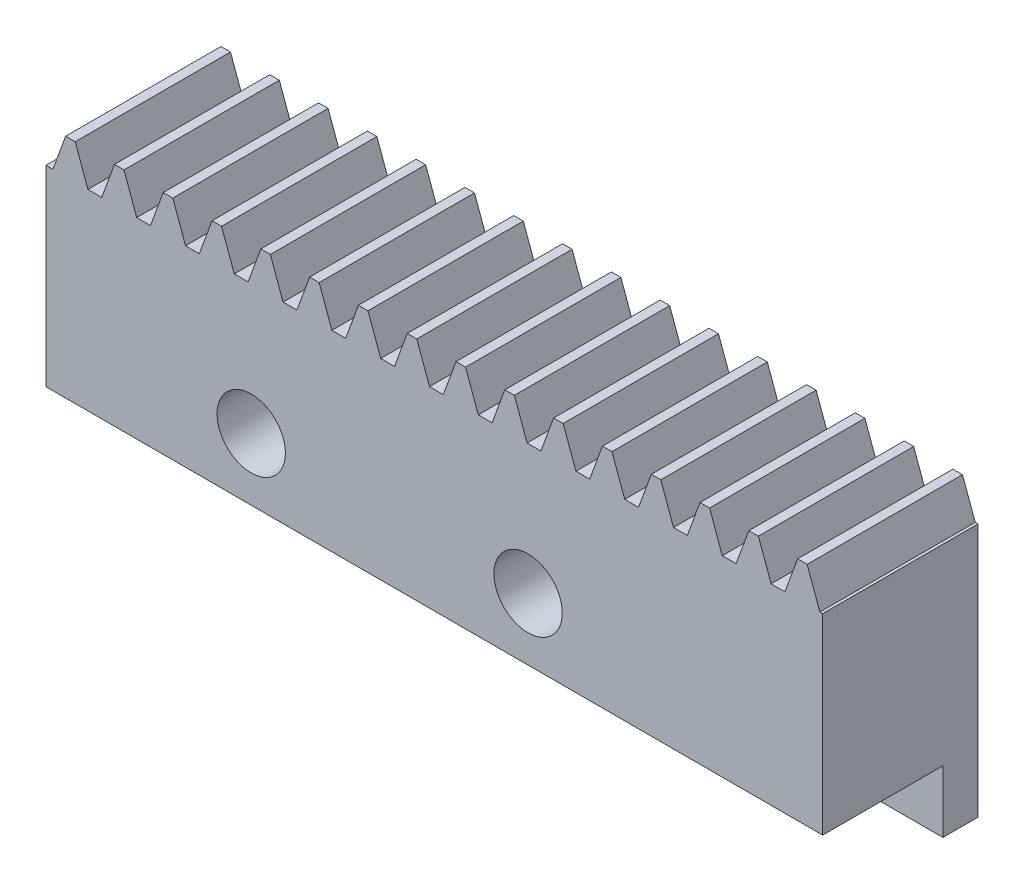
SolidWorks part; units mm, degrees
extrude "Blank" add sketch "BlankSke" against normal blind 4
sketch "BlankSke" plane through (0, 0, 0) normal (0, 0, 1) x (1, 0, 0)
  line L1 (0, 0) -> (25, 0)
  line L2 (0, 0) -> (0, 7.3)
  line L3 (0, 7.3) -> (25, 7.3)
  line L4 (25, 0) -> (25, 7.3)
  dimension "Length" = 25
  dimension "Blank_height" = 7.3
ref_plane "Plane1" through (0, 0, 0) normal (0, 0, 1) x (1, 0, 0)
ref_plane "Plane2" through (0, 0, 0) normal (0, 1, 0) x (1, 0, 0)
ref_plane "Plane3" through (0, 0, 0) normal (1, 0, 0) x (0, 0, -1)
sketch "HoldingSke" plane through (0, 0, 0) normal (0, 1, 0) x (1, 0, 0)
  line L0 (0, 0) -> (0.2783, 1.9805)
  line L1 (-15, 0) -> (100, 0) construction
  line L2 (0, 0) -> (-2.1039, 2.3779)
  line L3 (0, 0) -> (-11.863, 4.5341)
  line L4 (0, 0) -> (8.2587, 2.5249)
  line L5 (0, 0) -> (-23.7986, -8.8762)
  line L6 (0, 0) -> (-10.5278, -7.1032)
  line L9 (-71.009, 38.7566) -> (-47.5167, 47.3071)
  line L10 (-76.2, 2.8779) -> (-69.4, 2.8779)
  line L11 (0, 0) -> (-4, 0)
  line L12 (-76.2, 101.6) -> (-76.181, 101.6)
  line L13 (24.9733, 27.94) -> (52.9518, 28.4284)
  line L14 (24.9733, 27.94) -> (24.9743, 27.94)
  line L15 (24.9733, 27.94) -> (100.4006, 29.5858)
  circle A0 centre (0, 0) radius 19.05
  circle A1 centre (0, 0) radius 3.4
  circle A2 centre (0, 0) radius 12.7
  dimension "MPH" = 6.8
  dimension "Diameter" = 38.1
  dimension "Num_teeth" = 17
  dimension "Pitch" = 2
  dimension "Show_teeth" = 998
  dimension "Thickness" = 12.7
  dimension "Ap" = 20
  dimension "Pitch_height" = 6.8
  dimension "Width" = 4
  dimension "Backlash" = 0.019
  dimension "Addendum_fac" = 1
  dimension "Dedendum_fac" = 1.25
  dimension "Clearance_fac" = 0.25
  dimension "Dedendum_add" = 0.001
  dimension "Length" = 25
  dimension "Module" = 0.5
sketch "TooCutSkeIll" plane through (0, 0, 0) normal (0, 0, 1) x (1, 0, 0)
  line L0 (-0.6269, 7.2868) -> (-0.2524, 6.2579)
  line L1 (-0.134, 6.175) -> (0.134, 6.175)
  line L2 (0.2524, 6.2579) -> (0.6269, 7.2868)
  line L3 (25, 7.3) -> (0, 7.3) construction
  line L4 (0, 0) -> (0, 64.897) construction
  line L5 (-13.208, 6.8) -> (12.954, 6.8) construction
  line L6 (0, 0) -> (25, 0) construction
  line L7 (0.4497, 6.8) -> (0.4497, 48.7463) construction
  line L8 (-0.4497, 6.8) -> (-0.4497, 48.7463) construction
  line L9 (0.6457, 7.3) -> (0.6457, 7.3254)
  line L10 (-0.6457, 7.3) -> (-0.6457, 7.3254)
  line L11 (-0.6457, 7.3254) -> (0.6457, 7.3254)
  arc A0 (0.134, 6.175) -> (0.2524, 6.2579) centre (0.134, 6.301) ccw
  arc A1 (-0.2524, 6.2579) -> (-0.134, 6.175) centre (-0.134, 6.301) ccw
  arc A2 (0.6457, 7.3) -> (0.6269, 7.2868) centre (0.6457, 7.28) ccw
  arc A3 (-0.6269, 7.2868) -> (-0.6457, 7.3) centre (-0.6457, 7.28) ccw
  dimension "Pitch_height" = 6.8
  dimension "Addendum_plus" = 0.5254
  dimension "Pressure_angle" = 20
  dimension "Gap_width" = 0.8994
  dimension "Dedendum" = 0.625
extrude "ToothCutIll" [suppressed] cut sketch "TooCutSkeIll" against normal through all
sketch "TooCutSkeSim" plane through (0, 0, 0) normal (0, 0, 1) x (1, 0, 0)
  line L0 (0.2222, 6.175) -> (-0.2222, 6.175)
  line L1 (0.6409, 7.3254) -> (0.2222, 6.175)
  line L2 (0, 17.4625) -> (0, 53.467) construction
  line L3 (0.6409, 7.3254) -> (-0.6409, 7.3254)
  line L6 (-0.6409, 7.3254) -> (-0.2222, 6.175)
  line L9 (-0.4497, 6.8) -> (0.4497, 6.8) construction
  line L10 (0, 0) -> (25, 0) construction
  line L11 (0.4497, 6.8) -> (0.4497, 53.467) construction
  line L12 (-0.4497, 6.8) -> (-0.4497, 53.467) construction
  dimension "Pitch_height" = 6.8
  dimension "Addendum_plus" = 0.5254
  dimension "Pressure_angle" = 20
  dimension "Gap_width" = 0.8994
  dimension "Dedendum" = 0.625
extrude "ToothCutSim" cut sketch "TooCutSkeSim" against normal through all
pattern_linear "TeethCuts" count 17 spacing 1.5708 along (1, 0, 0) of "ToothCutIll", "ToothCutSim"
sketch "Sketch4" plane through (0, 0, 0) normal (0, -1, 0) x (1, 0, 0)
  line L0 (0, -50) -> (0, 50) construction
  line L1 (0, -4) -> (25, -4)
  line L2 (0, -4) -> (0, -2.87)
  line L3 (0, -2.87) -> (25, -2.87)
  line L4 (25, -4) -> (25, -2.87)
  line L5 (0, -4) -> (25, -4) construction
  line L6 (25, -4) -> (25, 0) construction
  dimension "D1" = 1.13
extrude "Boss-Extrude1" add sketch "Sketch4" along normal blind 2
sketch "Sketch7" plane through (0, 0, 0) normal (0, 0, 1) x (1, 0, 0)
  line L68 (25, 6.175) -> (24.9105, 6.175)
  line L69 (24.9105, 6.175) -> (24.5011, 7.3)
  line L70 (24.5011, 7.3) -> (24.1936, 7.3)
  line L71 (24.1936, 7.3) -> (23.7842, 6.175)
  line L72 (23.7842, 6.175) -> (23.3397, 6.175)
  line L73 (23.3397, 6.175) -> (22.9303, 7.3)
  line L74 (22.9303, 7.3) -> (22.6228, 7.3)
  line L75 (22.6228, 7.3) -> (22.2134, 6.175)
  line L76 (22.2134, 6.175) -> (21.7689, 6.175)
  line L77 (21.7689, 6.175) -> (21.3595, 7.3)
  line L78 (21.3595, 7.3) -> (21.052, 7.3)
  line L79 (21.052, 7.3) -> (20.6426, 6.175)
  line L80 (20.6426, 6.175) -> (20.1981, 6.175)
  line L81 (20.1981, 6.175) -> (19.7887, 7.3)
  line L82 (19.7887, 7.3) -> (19.4812, 7.3)
  line L83 (19.4812, 7.3) -> (19.0718, 6.175)
  line L84 (19.0718, 6.175) -> (18.6273, 6.175)
  line L85 (18.6273, 6.175) -> (18.2179, 7.3)
  line L86 (18.2179, 7.3) -> (17.9104, 7.3)
  line L87 (17.9104, 7.3) -> (17.501, 6.175)
  line L88 (17.501, 6.175) -> (17.0565, 6.175)
  line L89 (17.0565, 6.175) -> (16.6471, 7.3)
  line L90 (16.6471, 7.3) -> (16.3396, 7.3)
  line L91 (16.3396, 7.3) -> (15.9302, 6.175)
  line L92 (15.9302, 6.175) -> (15.4857, 6.175)
  line L93 (15.4857, 6.175) -> (15.0763, 7.3)
  line L94 (15.0763, 7.3) -> (14.7689, 7.3)
  line L95 (14.7689, 7.3) -> (14.3594, 6.175)
  line L96 (14.3594, 6.175) -> (13.9149, 6.175)
  line L97 (13.9149, 6.175) -> (13.5055, 7.3)
  line L98 (13.5055, 7.3) -> (13.1981, 7.3)
  line L99 (13.1981, 7.3) -> (12.7886, 6.175)
  line L100 (12.7886, 6.175) -> (12.3442, 6.175)
  line L101 (12.3442, 6.175) -> (11.9347, 7.3)
  line L102 (11.9347, 7.3) -> (11.6273, 7.3)
  line L103 (11.6273, 7.3) -> (11.2178, 6.175)
  line L104 (11.2178, 6.175) -> (10.7734, 6.175)
  line L105 (10.7734, 6.175) -> (10.3639, 7.3)
  line L106 (10.3639, 7.3) -> (10.0565, 7.3)
  line L107 (10.0565, 7.3) -> (9.647, 6.175)
  line L108 (9.647, 6.175) -> (9.2026, 6.175)
  line L109 (9.2026, 6.175) -> (8.7931, 7.3)
  line L110 (8.7931, 7.3) -> (8.4857, 7.3)
  line L111 (8.4857, 7.3) -> (8.0762, 6.175)
  line L112 (8.0762, 6.175) -> (7.6318, 6.175)
  line L113 (7.6318, 6.175) -> (7.2223, 7.3)
  line L114 (7.2223, 7.3) -> (6.9149, 7.3)
  line L115 (6.9149, 7.3) -> (6.5054, 6.175)
  line L116 (6.5054, 6.175) -> (6.061, 6.175)
  line L117 (6.061, 6.175) -> (5.6515, 7.3)
  line L118 (5.6515, 7.3) -> (5.3441, 7.3)
  line L119 (5.3441, 7.3) -> (4.9346, 6.175)
  line L120 (4.9346, 6.175) -> (4.4902, 6.175)
  line L121 (4.4902, 6.175) -> (4.0807, 7.3)
  line L122 (4.0807, 7.3) -> (3.7733, 7.3)
  line L123 (3.7733, 7.3) -> (3.3638, 6.175)
  line L124 (3.3638, 6.175) -> (2.9194, 6.175)
  line L125 (2.9194, 6.175) -> (2.5099, 7.3)
  line L126 (2.5099, 7.3) -> (2.2025, 7.3)
  line L127 (2.2025, 7.3) -> (1.793, 6.175)
  line L128 (1.793, 6.175) -> (1.3486, 6.175)
  line L129 (1.3486, 6.175) -> (0.9391, 7.3)
  line L130 (0.9391, 7.3) -> (0.6317, 7.3)
  line L131 (0.6317, 7.3) -> (0.2222, 6.175)
  line L132 (0.2222, 6.175) -> (0, 6.175)
  line L133 (0, 6.175) -> (0, 0)
  line L134 (0, 0) -> (25, 0)
  line L135 (25, 0) -> (25, 6.175)
  line L136 (25, 6.175) -> (24.9105, 6.175)
  line L137 (24.9105, 6.175) -> (24.5011, 7.3)
  line L138 (24.5011, 7.3) -> (24.1936, 7.3)
  line L139 (24.1936, 7.3) -> (23.7842, 6.175)
  line L140 (23.7842, 6.175) -> (23.3397, 6.175)
  line L141 (23.3397, 6.175) -> (22.9303, 7.3)
  line L142 (22.9303, 7.3) -> (22.6228, 7.3)
  line L143 (22.6228, 7.3) -> (22.2134, 6.175)
  line L144 (22.2134, 6.175) -> (21.7689, 6.175)
  line L145 (21.7689, 6.175) -> (21.3595, 7.3)
  line L146 (21.3595, 7.3) -> (21.052, 7.3)
  line L147 (21.052, 7.3) -> (20.6426, 6.175)
  line L148 (20.6426, 6.175) -> (20.1981, 6.175)
  line L149 (20.1981, 6.175) -> (19.7887, 7.3)
  line L150 (19.7887, 7.3) -> (19.4812, 7.3)
  line L151 (19.4812, 7.3) -> (19.0718, 6.175)
  line L152 (19.0718, 6.175) -> (18.6273, 6.175)
  line L153 (18.6273, 6.175) -> (18.2179, 7.3)
  line L154 (18.2179, 7.3) -> (17.9104, 7.3)
  line L155 (17.9104, 7.3) -> (17.501, 6.175)
  line L156 (17.501, 6.175) -> (17.0565, 6.175)
  line L157 (17.0565, 6.175) -> (16.6471, 7.3)
  line L158 (16.6471, 7.3) -> (16.3396, 7.3)
  line L159 (16.3396, 7.3) -> (15.9302, 6.175)
  line L160 (15.9302, 6.175) -> (15.4857, 6.175)
  line L161 (15.4857, 6.175) -> (15.0763, 7.3)
  line L162 (15.0763, 7.3) -> (14.7689, 7.3)
  line L163 (14.7689, 7.3) -> (14.3594, 6.175)
  line L164 (14.3594, 6.175) -> (13.9149, 6.175)
  line L165 (13.9149, 6.175) -> (13.5055, 7.3)
  line L166 (13.5055, 7.3) -> (13.1981, 7.3)
  line L167 (13.1981, 7.3) -> (12.7886, 6.175)
  line L168 (12.7886, 6.175) -> (12.3442, 6.175)
  line L169 (12.3442, 6.175) -> (11.9347, 7.3)
  line L170 (11.9347, 7.3) -> (11.6273, 7.3)
  line L171 (11.6273, 7.3) -> (11.2178, 6.175)
  line L172 (11.2178, 6.175) -> (10.7734, 6.175)
  line L173 (10.7734, 6.175) -> (10.3639, 7.3)
  line L174 (10.3639, 7.3) -> (10.0565, 7.3)
  line L175 (10.0565, 7.3) -> (9.647, 6.175)
  line L176 (9.647, 6.175) -> (9.2026, 6.175)
  line L177 (9.2026, 6.175) -> (8.7931, 7.3)
  line L178 (8.7931, 7.3) -> (8.4857, 7.3)
  line L179 (8.4857, 7.3) -> (8.0762, 6.175)
  line L180 (8.0762, 6.175) -> (7.6318, 6.175)
  line L181 (7.6318, 6.175) -> (7.2223, 7.3)
  line L182 (7.2223, 7.3) -> (6.9149, 7.3)
  line L183 (6.9149, 7.3) -> (6.5054, 6.175)
  line L184 (6.5054, 6.175) -> (6.061, 6.175)
  line L185 (6.061, 6.175) -> (5.6515, 7.3)
  line L186 (5.6515, 7.3) -> (5.3441, 7.3)
  line L187 (5.3441, 7.3) -> (4.9346, 6.175)
  line L188 (4.9346, 6.175) -> (4.4902, 6.175)
  line L189 (4.4902, 6.175) -> (4.0807, 7.3)
  line L190 (4.0807, 7.3) -> (3.7733, 7.3)
  line L191 (3.7733, 7.3) -> (3.3638, 6.175)
  line L192 (3.3638, 6.175) -> (2.9194, 6.175)
  line L193 (2.9194, 6.175) -> (2.5099, 7.3)
  line L194 (2.5099, 7.3) -> (2.2025, 7.3)
  line L195 (2.2025, 7.3) -> (1.793, 6.175)
  line L196 (1.793, 6.175) -> (1.3486, 6.175)
  line L197 (1.3486, 6.175) -> (0.9391, 7.3)
  line L198 (0.9391, 7.3) -> (0.6317, 7.3)
  line L199 (0.6317, 7.3) -> (0.2222, 6.175)
  line L200 (0.2222, 6.175) -> (0, 6.175)
  line L201 (0, 6.175) -> (0, 0)
  line L202 (0, 0) -> (25, 0)
  line L203 (25, 0) -> (25, 6.175)
  dimension "D1" = 0
extrude "Boss-Extrude2" add sketch "Sketch7" along normal blind 1
sketch "Sketch8" plane through (0, 0, 1) normal (0, 0, 1) x (1, 0, 0)
  line L0 (6.6057, 2) -> (3.6057, 2) construction
  line L1 (3.6057, 2) -> (18.1057, 2) construction
  line L2 (18.1057, 2) -> (15.5175, 2) construction
  line L3 (15.5175, 2) -> (14.4175, 2) construction
  line L4 (6.6057, 2) -> (3.6057, 2)
  line L5 (3.6057, 2) -> (18.1057, 2)
  line L6 (18.1057, 2) -> (15.5175, 2)
  line L7 (15.5175, 2) -> (14.4175, 2)
  circle A1 centre (15.5175, 2) radius 1.1
  circle A2 centre (15.5175, 2) radius 1.1
  circle A3 centre (15.5175, 2) radius 2.0275
  circle A4 centre (15.5175, 2) radius 2.0275
  circle A5 centre (6.6057, 2) radius 1.1
  circle A6 centre (6.6057, 2) radius 1.1
  dimension "D1" = 0
  dimension "D2" = 0
  dimension "D3" = 0
sketch "Sketch9" plane through (0, 0, 0) normal (0, 0, 1) x (1, 0, 0)
  line L4 (4, 2) -> (1, 2)
  line L5 (1, 2) -> (15.5, 2)
  line L6 (15.5, 2) -> (12.9118, 2)
  line L7 (12.9118, 2) -> (11.8118, 2)
  circle A2 centre (12.9118, 2) radius 1.1
  circle A4 centre (12.9118, 2) radius 2.0275
  circle A6 centre (4, 2) radius 1.1
extrude "Cut-Extrude1" cut sketch "Sketch8" against normal blind 10 contours L5 A2 | L5 A2 | L4 A6 L5 | L5 A6 L4
ref_plane "Plane4" through (0, 0, -4) normal (0, 0, -1) x (-1, 0, 0)
sketch "Sketch10" plane through (0, 0, -4) normal (0, 0, -1) x (-1, 0, 0)
  circle A0 centre (-6.6057, 2) radius 2
extrude "Cut-Extrude3" cut sketch "Sketch10" against normal blind 1
equation "' \"Module@HoldingSke\" = 6.35"
equation "' \"Num_teeth@HoldingSke\" = 12"
equation "' \"Ap@HoldingSke\" =  20"
equation "' \"Ap@HoldingSke\" = 20"
equation "' \"Width@HoldingSke\" = 0.25 * 25.4"
equation "' \"Show_teeth@HoldingSke\" = 500"
equation "' \"Backlash@HoldingSke\" = 0.009 * 25.4"
equation "' \"Addendum_fac@HoldingSke\" = 1.0"
equation "' \"Dedendum_fac@HoldingSke\" = 1.25"
equation "' \"Dedendum_add@HoldingSke\" = 0.00005 * 25.4"
equation "' \"Clearance_fac@HoldingSke\" = 0.25"
equation "' \"Pitch_height@HoldingSke\" = 1 * 25.4"
equation "' \"Length@HoldingSke\" = 4.71 * 25.4"
equation "\"Pitch@HoldingSke\" = 1 / \"Module@HoldingSke\""
equation "\"MPH@HoldingSke\" = \"Dedendum_fac@HoldingSke\" / \"Pitch@HoldingSke\" + 2 * \"Dedendum_add@HoldingSke\" + 0.002 * 25.4"
equation "\"MPH@HoldingSke\" = ((sgn( \"MPH@HoldingSke\" - \"Pitch_height@HoldingSke\")+1)*( \"MPH@HoldingSke\" - \"Pitch_height@HoldingSke\"))/2 + \"Pitch_height@HoldingSke\""
equation "\"Blank_height@BlankSke\" = \"Pitch_height@HoldingSke\" + \"Addendum_fac@HoldingSke\"  / \"Pitch@HoldingSke\" "
equation "\"Length@BlankSke\" =  \"Length@HoldingSke\""
equation "\"Face_width@Blank\" = \"Width@HoldingSke\""
equation "\"Pressure_angle@TooCutSkeIll\" = \"Ap@HoldingSke\""
equation "\"Addendum_plus@TooCutSkeIll\" =  \"Addendum_fac@HoldingSke\"  / \"Pitch@HoldingSke\" + 0.001 *25.4"
equation "\"Dedendum@TooCutSkeIll\" = \"Dedendum_fac@HoldingSke\"  / \"Pitch@HoldingSke\""
equation "\"Pitch_height@TooCutSkeIll\" =  \"MPH@HoldingSke\""
equation "\"Gap_width@TooCutSkeIll\" = 3.14159265 / 2 / \"Pitch@HoldingSke\" + 6 * \"Backlash@HoldingSke\""
equation "\"Pressure_angle@TooCutSkeSim\" = \"Ap@HoldingSke\""
equation "\"Addendum_plus@TooCutSkeSim\" =  \"Addendum_fac@HoldingSke\"  / \"Pitch@HoldingSke\" + 0.001 * 25.4"
equation "\"Dedendum@TooCutSkeSim\" = \"Dedendum_fac@HoldingSke\"  / \"Pitch@HoldingSke\""
equation "\"Pitch_height@TooCutSkeSim\" =  \"MPH@HoldingSke\""
equation "\"Gap_width@TooCutSkeSim\" = 3.14159265 / 2 / \"Pitch@HoldingSke\" + 6 * \"Backlash@HoldingSke\""
equation "\"Root_fillet@TooCutSkeIll\" = \"Clearance_fac@HoldingSke\" / \"Pitch@HoldingSke\" + \"Dedendum_add@HoldingSke\""
equation "\"Break_rad@TooCutSkeIll\" = 0.02 / \"Pitch@HoldingSke\" * 2"
equation "\"Linear_pitch@TeethCuts\" = 3.14159265 / \"Pitch@HoldingSke\""
equation "\"Num_teeth@HoldingSke\" = int( ( \"Length@HoldingSke\" + 0 ) / (3.14159265 / \"Pitch@HoldingSke\")) + 0.9999  + 1"
equation " \"Num_teeth@TeethCuts\" = int( \"Show_teeth@HoldingSke\" ) + 1"
equation " \"Num_teeth@TeethCuts\" = ((sgn( \"Num_teeth@TeethCuts\" - \"Num_teeth@HoldingSke\" )-1)*( \"Num_teeth@TeethCuts\" - \"Num_teeth@HoldingSke\" ))/-2+ \"Num_teeth@HoldingSke\""
equation " \"Num_teeth@TeethCuts\" = ((sgn( \"Num_teeth@TeethCuts\" - 2.0)+1)*( \"Num_teeth@TeethCuts\" - 2.0))/2 +2.0"
